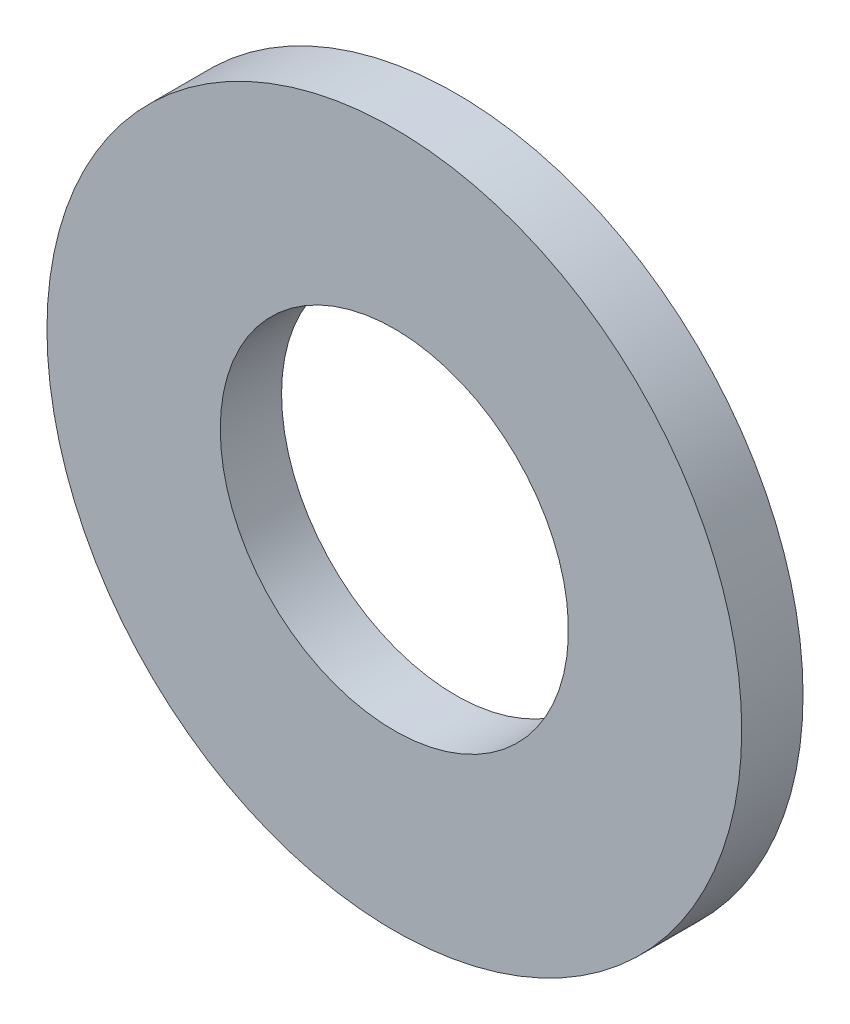
SolidWorks part; units mm, degrees
ref_plane "Piano frontale" through (0, 0, 0) normal (0, 0, 1) x (1, 0, 0)
ref_plane "Piano superiore" through (0, 0, 0) normal (0, 1, 0) x (1, 0, 0)
ref_plane "Piano destro" through (0, 0, 0) normal (1, 0, 0) x (0, 0, -1)
sketch "Schizzo2" plane through (0, 0, 0) normal (0, 0, 1) x (1, 0, 0)
  circle A0 centre (0, 0) radius 4.42
  circle A1 centre (0, 0) radius 2.215
  dimension "D1" = 4.43
  dimension "D2" = 8.84
extrude "Estrusione-Estrusione1" add sketch "Schizzo2" along normal blind 0.78
